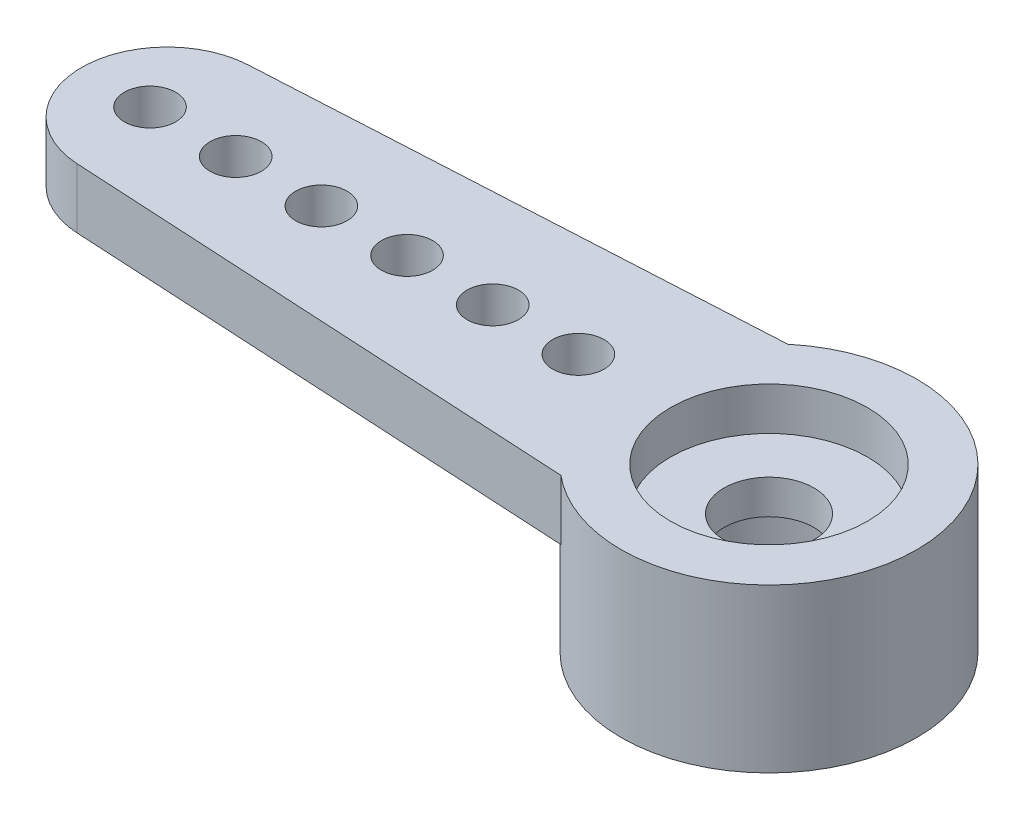
SolidWorks part; units mm, degrees
material "PVC Rígido"
ref_plane "Plano frontal" through (0, 0, 0) normal (0, 0, 1) x (1, 0, 0)
ref_plane "Plano superior" through (0, 0, 0) normal (0, 1, 0) x (1, 0, 0)
ref_plane "Plano direito" through (0, 0, 0) normal (1, 0, 0) x (0, 0, -1)
sketch "Esboço1" plane through (0, 0, 0) normal (0, 1, 0) x (1, 0, 0)
  line L0 (0, 0) -> (-14.05, 0) construction
  line L1 (-14.1591, 1.997) -> (-2.2091, 2.65)
  line L2 (-2.2091, -2.65) -> (-14.1591, -1.997)
  arc A0 (-2.2091, -2.65) -> (-2.2091, 2.65) centre (0, 0) ccw
  arc A1 (-14.1591, 1.997) -> (-14.1591, -1.997) centre (-14.05, 0) ccw
  dimension "D1" = 6.9
  dimension "D2" = 4
  dimension "D3" = 19.5
  dimension "D4" = 5.3
extrude "Ressalto-extrusão1" add sketch "Esboço1" against normal blind 1.4
sketch "Esboço2" plane through (0, -1.4, 0) normal (0, -1, 0) x (1, 0, 0)
  arc A0 (-2.2091, -2.65) -> (-2.2091, 2.65) centre (0, 0) ccw construction
  circle A1 centre (0, 0) radius 3.45
extrude "Ressalto-extrusão2" add sketch "Esboço2" along normal offset from surface (2.4 mm away) 3.8 up to face at (-7.242, 0, 0)
hole_wizard "Furo4" positions "Esboço9" profile "Esboço10" legacy end condition through all
sketch "Esboço9" plane through (0, 0, 0) normal (0, 1, 0) x (1, 0, 0)
  line L1 (-14.45, 0) -> (0, 0) construction
  arc A2 (-14.1591, 1.997) -> (-14.1591, -1.997) centre (-14.05, 0) ccw construction
  point P0 (-14.45, 0)
  point P19 (-16.05, 0)
  dimension "D1" = 1.6
sketch "Esboço10" plane through (-14.45, 0, 0) normal (1, 0, 0) x (0, 0, 1)
  line L0 (0, 0) -> (0, 3.8)
  line L1 (0, 3.8) -> (0.6, 3.8)
  line L2 (0.6, 3.8) -> (0.6, 0)
  line L3 (0.6, 0) -> (0, 0)
  line L4 (0, 110) -> (0, -10) construction
  dimension "Diameter" = 1.2
  dimension "Depth" = 3.8
pattern_linear "Padrão linear1" count 6 spacing 2 along (1, 0, 0) of "Furo4"
hole_wizard "Furo1" positions "Esboço3" profile "Esboço4" legacy
sketch "Esboço3" plane through (0, -3.8, 0) normal (0, -1, 0) x (-1, 0, 0)
  point P0 (0, 0)
sketch "Esboço4" plane through (0, -3.8, 0) normal (1, 0, 0) x (0, 0, -1)
  line L0 (0, 0) -> (0, 2)
  line L1 (0, 2) -> (2.475, 2)
  line L2 (2.475, 2) -> (2.475, 0)
  line L3 (2.475, 0) -> (0, 0)
  line L4 (0, 110) -> (0, -10) construction
  dimension "Diameter" = 4.95
  dimension "Depth" = 2
hole_wizard "Furo2" positions "Esboço5" profile "Esboço6" legacy
sketch "Esboço5" plane through (0, 0, 0) normal (0, 1, 0) x (1, 0, 0)
  point P0 (0, 0)
sketch "Esboço6" plane through (0, 0, 0) normal (1, 0, 0) x (0, 0, 1)
  line L0 (0, 0) -> (0, 1)
  line L1 (0, 1) -> (2.3, 1)
  line L2 (2.3, 1) -> (2.3, 0)
  line L3 (2.3, 0) -> (0, 0)
  line L4 (0, 110) -> (0, -10) construction
  dimension "Diameter" = 4.6
  dimension "Depth" = 1
hole_wizard "Furo3" positions "Esboço7" profile "Esboço8" legacy end condition through all
sketch "Esboço7" plane through (0, 0, 0) normal (0, 1, 0) x (1, 0, 0)
  point P0 (0, 0)
sketch "Esboço8" plane through (0, 0, 0) normal (1, 0, 0) x (0, 0, 1)
  line L0 (0, 0) -> (0, 3.8)
  line L1 (0, 3.8) -> (1.05, 3.8)
  line L2 (1.05, 3.8) -> (1.05, 0)
  line L3 (1.05, 0) -> (0, 0)
  line L4 (0, 110) -> (0, -10) construction
  dimension "Diameter" = 2.1
  dimension "Depth" = 3.8
sketch "Esboço11" plane through (0, -3.8, 0) normal (0, -1, 0) x (1, 0, 0)
  line L0 (-0.0981, 2.4731) -> (0, 2.375)
  line L1 (0, 2.375) -> (0.0981, 2.4731)
  line L2 (0, 0) -> (0, 2.475) construction
  circle A0 centre (0, 0) radius 2.375 construction
  circle A1 centre (0, 0) radius 2.475
  arc A2 (0.0981, 2.4731) -> (-0.0981, 2.4731) centre (0, 0) ccw
  dimension "D3" = 4.75
  dimension "D2" = 0.1
  dimension "D1" = 0
extrude "Ressalto-extrusão3" [suppressed] add sketch "Esboço11" against normal up to surface (2 mm away)
pattern_circular "PadrãoCircular1" [suppressed] count 60 over 360
